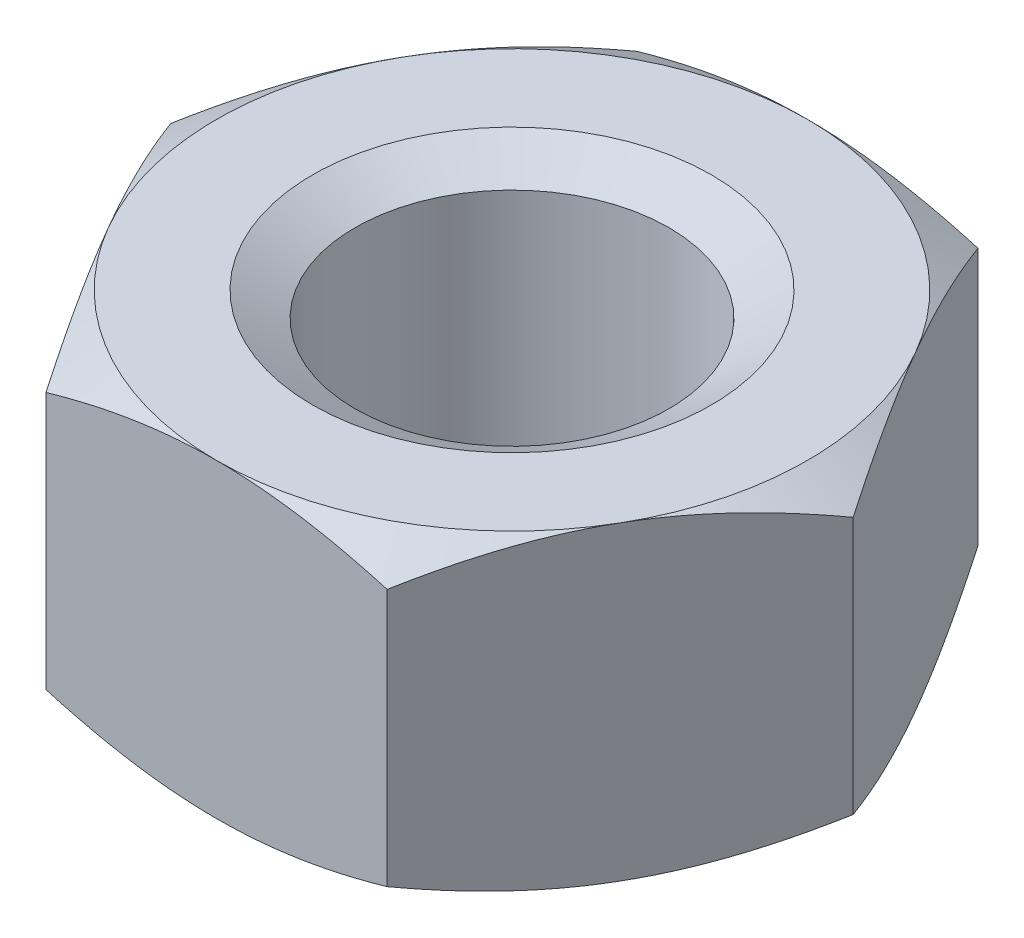
SolidWorks part; units mm, degrees
ref_plane "Přední rovina" through (0, 0, 0) normal (0, 0, 1) x (1, 0, 0)
ref_plane "Vrchní rovina" through (0, 0, 0) normal (0, 1, 0) x (1, 0, 0)
ref_plane "Pravá rovina" through (0, 0, 0) normal (1, 0, 0) x (0, 0, -1)
sketch "Skica1" plane through (0, 0, 0) normal (0, 1, 0) x (1, 0, 0)
  line L1 (9.2376, 0) -> (4.6188, 8)
  line L2 (4.6188, 8) -> (-4.6188, 8)
  line L3 (-4.6188, 8) -> (-9.2376, 0)
  line L4 (-9.2376, 0) -> (-4.6188, -8)
  line L5 (-4.6188, -8) -> (4.6188, -8)
  line L6 (4.6188, -8) -> (9.2376, 0)
  circle A0 centre (0, 0) radius 8 construction
  dimension "s" = 16
extrude "Vysunout1" add sketch "Skica1" along normal mid plane 8.4
sketch "Skica2" plane through (0, 0, 0) normal (1, 0, 0) x (0, 0, -1)
  line L0 (8, 4.2) -> (15.2746, 4.2)
  line L1 (15.2746, 4.2) -> (15.2746, -4.2)
  line L2 (15.2746, -4.2) -> (8, -4.2)
  line L3 (8, -4.2) -> (15.2746, 0)
  line L4 (15.2746, 0) -> (8, 4.2)
  line L5 (0, 4.2) -> (0, 0) construction
  dimension "D1" = 30
revolve "Odebrat otočením1" cut sketch "Skica2" angle 360 about L5
sketch "Skica3" plane through (0, 4.2, 0) normal (0, 1, 0) x (-1, 0, 0)
  circle A0 centre (0, 0) radius 4.25
  dimension "M´" = 8.5
extrude "Odebrat vysunutím1" cut sketch "Skica3" against normal through all
cosmetic thread "Kosmetický závit1" parameters "M"=10
sketch "Skica4" plane through (0, 4.2, 0) normal (0, 1, 0) x (-1, 0, 0)
  circle A0 centre (0, 0) radius 5.4
  dimension "da" = 10.8
extrude "Odebrat vysunutím2" cut sketch "Skica4" against normal up to next (8.4 mm away) draft 60
mirror "Zrcadlit1" about plane through (0, 0, 0) normal (0, 1, 0) of "Odebrat vysunutím2"
